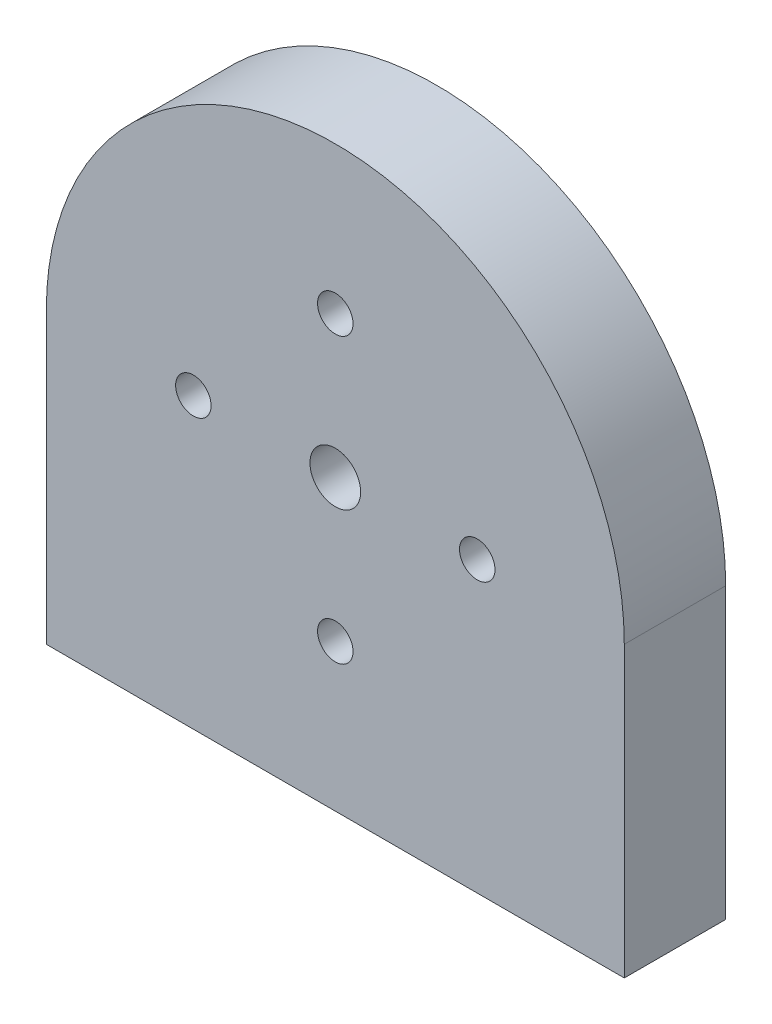
SolidWorks part; units mm, degrees
ref_plane "Спереди" through (0, 0, 0) normal (0, 0, 1) x (1, 0, 0)
ref_plane "Сверху" through (0, 0, 0) normal (0, 1, 0) x (1, 0, 0)
ref_plane "Справа" through (0, 0, 0) normal (1, 0, 0) x (0, 0, -1)
sketch "Эскиз1" plane through (0, 0, 0) normal (0, 0, 1) x (1, 0, 0)
  line L0 (-28.5, 0) -> (-28.5, -28.5)
  line L1 (-28.5, -28.5) -> (28.5, -28.5)
  line L2 (28.5, -28.5) -> (28.5, 0)
  arc A0 (28.5, 0) -> (-28.5, 0) centre (0, 0) ccw
  circle A1 centre (0, 0) radius 14 construction
  circle A2 centre (0, 14) radius 1.75
  circle A6 centre (14, 0) radius 1.75
  circle A7 centre (0, -14) radius 1.75
  circle A8 centre (-14, 0) radius 1.75
  circle A9 centre (0, 0) radius 2.5
  dimension "D1" = 57
  dimension "D2" = 28
  dimension "D3" = 3.5
  dimension "D5" = 5
  dimension "D4" = 4
extrude "Бобышка-Вытянуть1" add sketch "Эскиз1" along normal blind 10
sketch "Эскиз2" plane through (0, 0, 10) normal (0, 0, 1) x (1, 0, 0)
  line L0 (-28.5, -6.2988) -> (28.5, -6.2988)
  line L1 (-28.5, 0) -> (-28.5, -28.5) construction
  line L2 (28.5, -28.5) -> (28.5, 0) construction
  point P6 (28.5, -3.1445)
equation "\"Ball_bearing_D\"= 12.7"
equation "\"Ball_bearing_h1\"= 9"
equation "\"Ball_bearing_d1\"= 5.9"
equation "\"Ball_bearing_d2\"= 18"
equation "\"Ball_bearing_h2\"= 6.6"
equation "\"Brake_tube_d1\"= 2"
equation "\"Brake_tube_d2\"= 5"
equation "\"Brake_tube_h\"= 20"
equation "\"print_offset\"= 0.5"
equation "\"angle_mount\"=25"
equation "\"inner_distance\"= 20"
equation "\"D3@Эскиз1\"=\"print_offset\"+3"
equation "\"D5@Эскиз1\"=\"Brake_tube_d2\""
